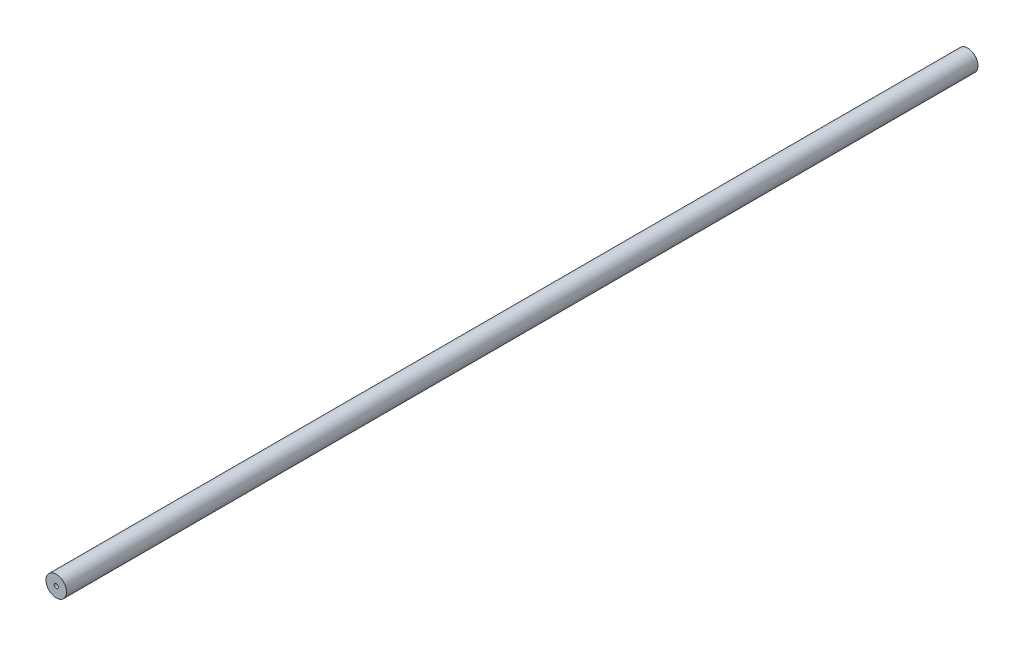
SolidWorks part; units mm, degrees
material "Balsa"
ref_plane "Front Plane" through (0, 0, 0) normal (0, 0, 1) x (1, 0, 0)
ref_plane "Top Plane" through (0, 0, 0) normal (0, 1, 0) x (1, 0, 0)
ref_plane "Right Plane" through (0, 0, 0) normal (1, 0, 0) x (0, 0, -1)
sketch "Sketch2" plane through (0, 0, 0) normal (0, 0, 1) x (1, 0, 0)
  circle A0 centre (0, 0) radius 5.588
  dimension "D1" = 11.176
extrude "Boss-Extrude1" add sketch "Sketch2" along normal mid plane 495.3
sketch "Sketch7" plane through (0, 0, 247.65) normal (0, 0, 1) x (1, 0, 0)
  circle A0 centre (0, 0) radius 1.143
  dimension "D1" = 2.286
extrude "Cut-Extrude3" cut sketch "Sketch7" against normal blind 25.4
sketch "Sketch9" plane through (0, 0, -247.65) normal (0, 0, -1) x (-1, 0, 0)
  circle A0 centre (0, 0) radius 1.143
  point P3 (0, 0)
  dimension "D1" = 2.286
extrude "Cut-Extrude4" cut sketch "Sketch9" against normal blind 25.4
